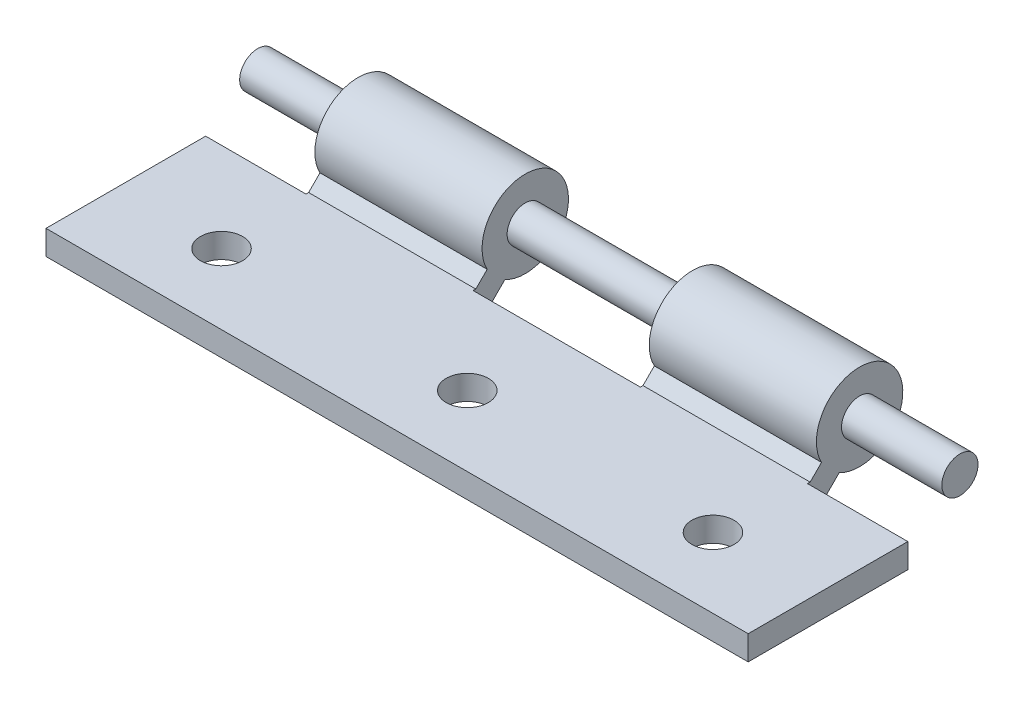
SolidWorks part; units mm, degrees
ref_plane "Front" through (0, 0, 0) normal (0, 0, 1) x (1, 0, 0)
ref_plane "Top" through (0, 0, 0) normal (0, 1, 0) x (1, 0, 0)
ref_plane "Right" through (0, 0, 0) normal (1, 0, 0) x (0, 0, -1)
sketch "Sketch1" plane through (0, 0, 0) normal (1, 0, 0) x (0, 0, -1)
  line L0 (-5.4743, -8) -> (-2.8996, -5.4253)
  line L2 (-30.1625, -4.5202) -> (-7.0459, -4.5202)
  line L3 (-5.4743, -8) -> (-30.1625, -8)
  line L4 (-30.1625, -4.5202) -> (-30.1625, -8)
  line L5 (-7.0459, -4.5202) -> (-5.4253, -2.8996)
  line L6 (-30.1625, -8) -> (30.1625, -8) construction
  line L7 (0, 0) -> (-6.2601, -6.2601) construction
  line L8 (-6.2601, -6.2601) -> (-30.1625, -6.2601) construction
  line L9 (-7.0459, -4.5202) -> (-5.4743, -8) construction
  circle A0 centre (0, 0) radius 2.5797
  arc A2 (-2.8996, -5.4253) -> (-5.4253, -2.8996) centre (0, 0) ccw
  point P1 (0, -8)
  dimension "D1" = 3.5719
  dimension "Pin Dia" = 5.1594
  dimension "D2" = 12.3031
  dimension "Th" = 3.4798
  dimension "D3" = 8
  dimension "Open Wd" = 60.325
  dimension "D4" = 45
extrude "Left Leaf" add sketch "Sketch1" along normal mid plane 100.0125
sketch "Sketch2" plane through (0, 0, 0) normal (0, 1, 0) x (1, 0, 0)
  line L0 (-50.0062, -6.1516) -> (50.0062, -6.1516) construction
  line L2 (50.0062, 6.1516) -> (-50.0062, 6.1516) construction
  line L3 (50.0062, -7.4216) -> (35.7187, -7.4216)
  line L4 (50.0062, -7.4216) -> (50.0062, 6.1516)
  line L5 (50.0062, 6.1516) -> (35.7187, 6.1516)
  line L6 (35.7187, -7.4216) -> (35.7187, 6.1516)
  line L7 (-35.7187, 6.1516) -> (0, 6.1516) construction
  line L8 (-50.0062, -7.4216) -> (-35.7187, -7.4216)
  line L9 (-50.0062, -7.4216) -> (-50.0062, 6.1516)
  line L10 (-50.0062, 6.1516) -> (-35.7187, 6.1516)
  line L11 (-35.7187, -7.4216) -> (-35.7187, 6.1516)
  line L12 (0, -30.1625) -> (0, 30.1625) construction
  line L13 (-50.0062, 6.1516) -> (-50.0062, -6.1516) construction
  line L14 (0, 6.1516) -> (35.7187, 6.1516) construction
  line L15 (-35.7187, 6.1516) -> (-11.9062, 6.1516) construction
  line L16 (-11.9062, 6.1516) -> (11.9062, 6.1516)
  line L17 (-11.9062, 6.1516) -> (-11.9062, -7.4216)
  line L18 (-11.9062, -7.4216) -> (11.9062, -7.4216)
  line L19 (11.9062, 6.1516) -> (11.9062, -7.4216)
  dimension "D1" = 1.27
  dimension "D2" = 14.2875
extrude "Cut-Extrude1" cut sketch "Sketch2" against normal through all and the other way through all
sketch "Sketch3" plane through (0, 0, 0) normal (1, 0, 0) x (0, 0, -1)
  line L0 (0, 15.7543) -> (0, -15.7543) construction
  line L1 (5.4743, -8) -> (30.1625, -8)
  line L2 (-30.1625, -8) -> (30.1625, -8) construction
  line L4 (30.1625, -8) -> (30.1625, -4.5202)
  line L5 (30.1625, -4.5202) -> (7.0459, -4.5202)
  line L6 (5.4253, -2.8996) -> (7.0459, -4.5202)
  line L7 (5.4743, -8) -> (2.8996, -5.4253)
  line L9 (-5.4743, -8) -> (-30.1625, -8) construction
  line L10 (-5.4743, -8) -> (-2.8996, -5.4253) construction
  line L11 (-30.1625, -4.5202) -> (-7.0459, -4.5202) construction
  line L13 (-30.1625, -4.5202) -> (-30.1625, -8) construction
  line L14 (-7.0459, -4.5202) -> (-5.4253, -2.8996) construction
  arc A2 (-2.8996, -5.4253) -> (-5.4253, -2.8996) centre (0, 0) ccw construction
  arc A3 (2.8996, -5.4253) -> (5.4253, -2.8996) centre (0, 0) cw
  circle A4 centre (0, 0) radius 2.5797
  circle A5 centre (0, 0) radius 2.5797 construction
sketch "Sketch9" plane through (0, 0, 0) normal (0, 1, 0) x (1, 0, 0)
  line L0 (0, 6.1516) -> (35.7187, 6.1516) construction
  line L1 (-37.6237, 7.4216) -> (37.6237, 7.4216) construction
  line L2 (-37.6237, 7.4216) -> (-37.6237, -7.4216)
  line L3 (-37.6237, -7.4216) -> (37.6237, -7.4216) construction
  line L4 (37.6237, 7.4216) -> (37.6237, -7.4216)
  line L5 (-37.6237, 7.4216) -> (-10.0012, 7.4216)
  line L6 (50.0062, -7.4216) -> (35.7187, -7.4216) construction
  line L7 (35.7187, -7.4216) -> (35.7187, 6.1516) construction
  line L8 (37.6237, 0) -> (35.7187, 0) construction
  line L9 (-37.6237, 0) -> (-35.7187, 0) construction
  line L10 (-35.7187, -7.4216) -> (-35.7187, 6.1516) construction
  line L11 (-10.0012, 7.4216) -> (-10.0012, -7.4216)
  line L12 (-10.0012, -7.4216) -> (-37.6237, -7.4216)
  line L13 (37.6237, 7.4216) -> (10.0013, 7.4216)
  line L14 (10.0013, 7.4216) -> (10.0013, -7.4216)
  line L15 (10.0013, -7.4216) -> (37.6237, -7.4216)
  line L16 (-35.7187, 0) -> (-11.9062, 0) construction
  line L17 (-11.9062, 0) -> (-10.0013, 0) construction
  line L18 (-11.9062, 6.1516) -> (-11.9062, -7.4216) construction
  line L19 (10.0013, 0) -> (11.9062, 0) construction
  line L20 (11.9062, 0) -> (35.7187, 0) construction
  line L21 (11.9062, 6.1516) -> (11.9062, -7.4216) construction
  point P12 (0, 7.4216)
  point P17 (-23.8125, 0)
  point P25 (36.6712, 0)
  point P26 (-36.6712, 0)
  point P32 (-10.9537, 0)
  point P33 (23.8125, 0)
  point P34 (10.9537, 0)
  dimension "D1" = 1.27
  dimension "D2" = 1.905
sketch "Sketch10" plane through (0, 0, 0) normal (1, 0, 0) x (0, 0, -1)
  circle A0 centre (0, 0) radius 2.5797
  circle A1 centre (0, 0) radius 2.5797 construction
extrude "Extrude1" add sketch "Sketch10" along normal mid plane 100.0125 separate body
ref_plane "Plane1" through (36.6712, 0, 0) normal (1, 0, 0) x (0, 0, -1)
ref_plane "Plane2" through (-23.8125, 0, 0) normal (1, 0, 0) x (0, 0, -1)
ref_plane "Plane3" through (23.8125, 0, 0) normal (1, 0, 0) x (0, 0, -1)
ref_plane "Plane4" through (-10.9537, 0, 0) normal (1, 0, 0) x (0, 0, -1)
ref_plane "Plane5" through (10.9537, 0, 0) normal (1, 0, 0) x (0, 0, -1)
sketch "Sketch11" plane through (0, -4.5202, 0) normal (0, 1, 0) x (1, 0, 0)
  line L0 (-50.0062, -20.1625) -> (50.0062, -20.1625) construction
  line L1 (-50.0062, -7.4216) -> (-50.0062, -30.1625) construction
  line L2 (50.0062, -7.4216) -> (50.0062, -30.1625) construction
  line L3 (50.0062, -30.1625) -> (-50.0062, -30.1625) construction
  line L4 (-15.0062, -20.1625) -> (85.0063, -20.1625) construction
  line L5 (19.9938, -20.1625) -> (120.0063, -20.1625) construction
  circle A0 centre (-35.0062, -20.1625) radius 3
  circle A1 centre (-0.0062, -20.1625) radius 3
  circle A2 centre (34.9938, -20.1625) radius 3
  dimension "D2" = 6
  dimension "D1" = 10
  dimension "D3" = 15
  dimension "D4" = 3
extrude "Cut-Extrude2" cut sketch "Sketch11" against normal blind 10
